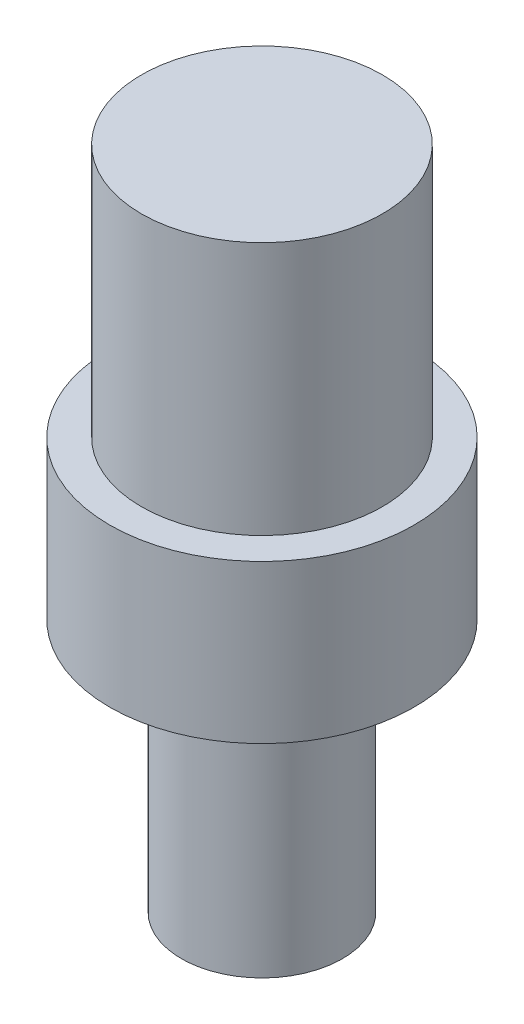
SolidWorks part; units mm, degrees
ref_plane "Front Plane" through (0, 0, 0) normal (0, 0, 1) x (1, 0, 0)
ref_plane "Top Plane" through (0, 0, 0) normal (0, 1, 0) x (1, 0, 0)
ref_plane "Right Plane" through (0, 0, 0) normal (1, 0, 0) x (0, 0, -1)
sketch "Sketch1" plane through (0, 0, 0) normal (0, 1, 0) x (1, 0, 0)
  circle A0 centre (0, 0) radius 6
  dimension "D1" = 12
extrude "Boss-Extrude1" add sketch "Sketch1" along normal mid plane 6.22
sketch "Sketch2" plane through (0, 3.11, 0) normal (0, 1, 0) x (1, 0, 0)
  circle A0 centre (0, 0) radius 4.75
  dimension "D1" = 9.5
extrude "Boss-Extrude2" add sketch "Sketch2" along normal blind 10
sketch "Sketch3" plane through (0, -3.11, 0) normal (0, -1, 0) x (1, 0, 0)
  circle A0 centre (0, 0) radius 3.175
  dimension "D1" = 6.35
extrude "Boss-Extrude3" add sketch "Sketch3" along normal blind 10
